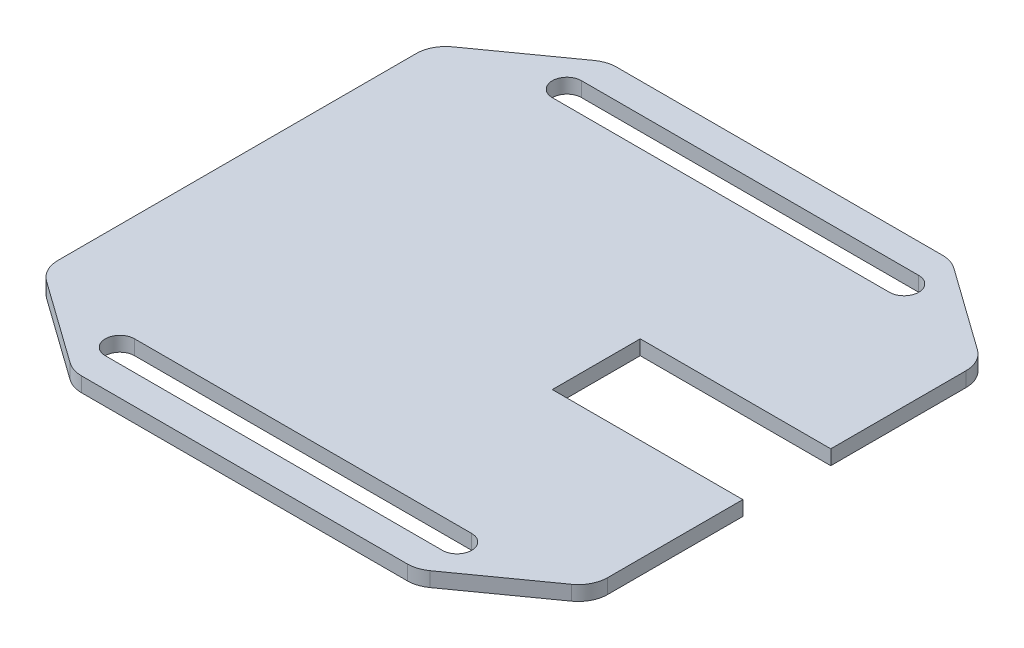
SolidWorks part; units mm, degrees
ref_plane "前视基准面" through (0, 0, 0) normal (0, 0, 1) x (1, 0, 0)
ref_plane "上视基准面" through (0, 0, 0) normal (0, 1, 0) x (1, 0, 0)
ref_plane "右视基准面" through (0, 0, 0) normal (1, 0, 0) x (0, 0, -1)
sketch "草图1" plane through (0, 0, 0) normal (0, 1, 0) x (1, 0, 0)
  line L1 (-18.75, 18.25) -> (18.75, 18.25)
  line L2 (-18.75, 18.25) -> (-18.75, -18.25)
  line L3 (-18.75, -18.25) -> (18.75, -18.25)
  line L4 (18.75, 18.25) -> (18.75, -18.25)
  line L5 (-18.75, 18.25) -> (18.75, -18.25) construction
  line L6 (-18.75, -18.25) -> (18.75, 18.25) construction
  point P0 (0, 0)
  dimension "D1" = 37.5
  dimension "D2" = 36.5
extrude "凸台-拉伸1" add sketch "草图1" along normal blind 1
sketch "草图2" plane through (0, 1, 0) normal (0, 1, 0) x (1, 0, 0)
  line L0 (18.75, 18.25) -> (-18.75, 18.25) construction
  line L1 (-18.75, 18.25) -> (-18.75, -18.25) construction
  line L2 (-11.75, 18.25) -> (-18.75, 13.25)
  line L3 (-18.75, 13.25) -> (-18.75, 18.25)
  line L4 (-18.75, 18.25) -> (-11.75, 18.25)
  line L5 (0, 18.25) -> (0, -18.25) construction
  line L6 (-18.75, -18.25) -> (18.75, -18.25) construction
  line L7 (-18.75, 0) -> (18.75, 0) construction
  line L8 (18.75, -18.25) -> (18.75, 18.25) construction
  line L9 (18.75, 18.25) -> (11.75, 18.25)
  line L10 (18.75, 13.25) -> (18.75, 18.25)
  line L11 (11.75, 18.25) -> (18.75, 13.25)
  line L12 (11.75, -18.25) -> (18.75, -13.25)
  line L13 (18.75, -13.25) -> (18.75, -18.25)
  line L14 (18.75, -18.25) -> (11.75, -18.25)
  line L15 (-18.75, -18.25) -> (-11.75, -18.25)
  line L16 (-18.75, -13.25) -> (-18.75, -18.25)
  line L17 (-11.75, -18.25) -> (-18.75, -13.25)
  point P0 (-11.75, 18.25)
  point P1 (-18.75, 13.25)
  dimension "D1" = 7
  dimension "D2" = 5
extrude "切除-拉伸1" cut sketch "草图2" against normal blind 1
sketch "草图3" plane through (0, 1, 0) normal (0, 1, 0) x (1, 0, 0)
  line L0 (-11.5, 15.25) -> (11.5, 15.25) construction
  line L1 (-11.5, 16.25) -> (11.5, 16.25)
  line L2 (-11.5, 14.25) -> (11.5, 14.25)
  line L3 (0, 18.25) -> (0, -18.25) construction
  line L4 (11.75, 18.25) -> (-11.75, 18.25) construction
  line L5 (-11.75, -18.25) -> (11.75, -18.25) construction
  line L6 (-18.75, 0) -> (18.75, 0) construction
  line L7 (-18.75, 13.25) -> (-18.75, -13.25) construction
  line L8 (18.75, -13.25) -> (18.75, 13.25) construction
  line L9 (-11.5, -15.25) -> (11.5, -15.25) construction
  line L10 (-11.5, -16.25) -> (11.5, -16.25)
  line L11 (-11.5, -14.25) -> (11.5, -14.25)
  arc A0 (-11.5, 16.25) -> (-11.5, 14.25) centre (-11.5, 15.25) ccw
  arc A1 (11.5, 14.25) -> (11.5, 16.25) centre (11.5, 15.25) ccw
  arc A2 (-11.5, -16.25) -> (-11.5, -14.25) centre (-11.5, -15.25) cw
  arc A3 (11.5, -14.25) -> (11.5, -16.25) centre (11.5, -15.25) cw
  point P2 (0, 15.25)
  point P22 (0, -15.25)
  dimension "D1" = 23
  dimension "D2" = 2
  dimension "D3" = 2
extrude "切除-拉伸2" cut sketch "草图3" against normal blind 1
fillet "圆角1" radius 2 8 edges at (-18.75, 0.5, -13.25) (-11.75, 0.5, -18.25) (11.75, 0.5, -18.25) (18.75, 0.5, -13.25) (18.75, 0.5, 13.25) (11.75, 0.5, 18.25) (-11.75, 0.5, 18.25) (-18.75, 0.5, 13.25)
sketch "草图4" plane through (0, 1, 0) normal (0, 1, 0) x (1, 0, 0)
  line L0 (-18.75, 0) -> (18.75, 0) construction
  line L1 (-18.75, 12.2208) -> (-18.75, -12.2208) construction
  line L2 (18.75, -12.2208) -> (18.75, 12.2208) construction
  line L4 (5.75, 3) -> (18.75, 3)
  line L5 (5.75, 3) -> (5.75, -3)
  line L6 (5.75, -3) -> (18.75, -3)
  line L7 (18.75, 3) -> (18.75, -3)
  line L8 (5.75, 3) -> (18.75, -3) construction
  line L9 (5.75, -3) -> (18.75, 3) construction
  point P6 (12.25, 0)
  dimension "D1" = 13
  dimension "D2" = 6
extrude "切除-拉伸3" cut sketch "草图4" against normal blind 1
